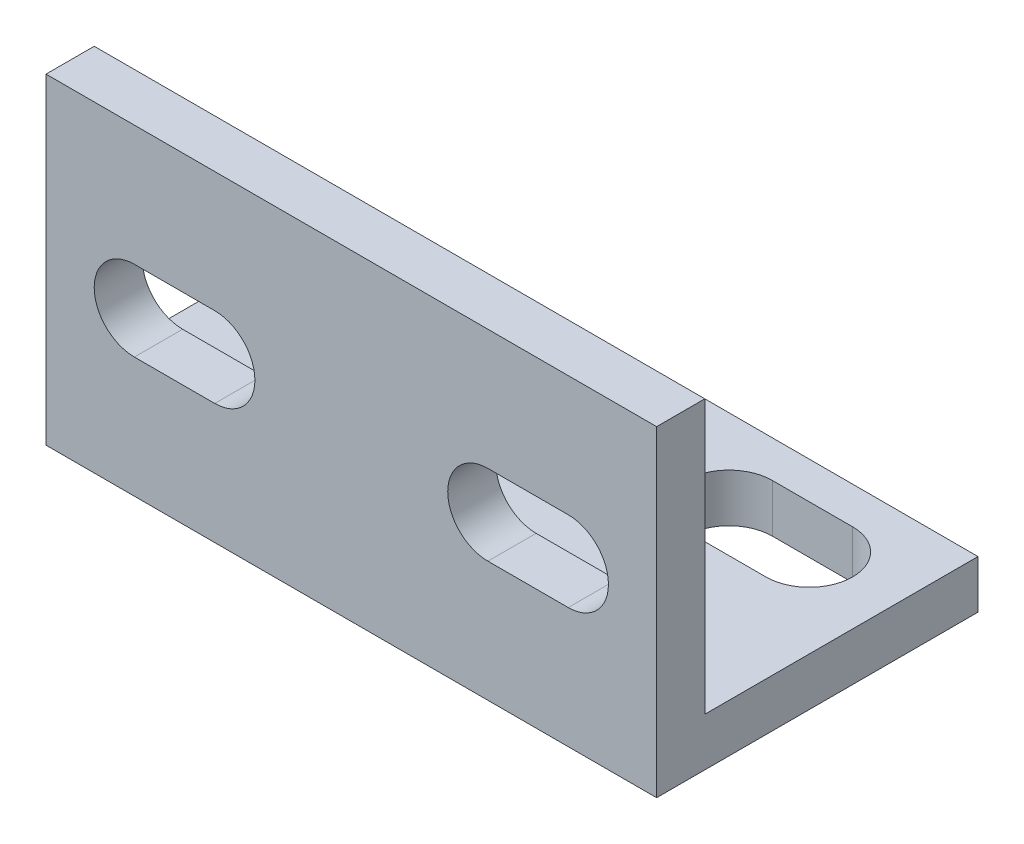
SolidWorks part; units mm, degrees
ref_plane "Front Plane" through (0, 0, 0) normal (0, 0, 1) x (1, 0, 0)
ref_plane "Top Plane" through (0, 0, 0) normal (0, 1, 0) x (1, 0, 0)
ref_plane "Right Plane" through (0, 0, 0) normal (1, 0, 0) x (0, 0, -1)
sketch "Sketch1" plane through (0, 0, 0) normal (1, 0, 0) x (0, 0, -1)
  line L0 (0, 0) -> (-17, 0)
  line L1 (-17, 0) -> (-17, 17)
  line L2 (-17, 17) -> (-20, 17)
  line L3 (-20, 17) -> (-20, -3)
  line L4 (0, 0) -> (0, -3)
  line L5 (0, -3) -> (-20, -3)
  dimension "D1" = 3
  dimension "D2" = 3
  dimension "D3" = 20
  dimension "D4" = 20
extrude "Boss-Extrude1" add sketch "Sketch1" along normal blind 38
sketch "Sketch2" plane through (0, 0, 0) normal (0, 1, 0) x (1, 0, 0)
  line L0 (0, -5) -> (38, -5) construction
  line L1 (0, 0) -> (0, -17) construction
  line L2 (38, 0) -> (38, -17) construction
  line L3 (38, 0) -> (0, 0) construction
  line L4 (5.5, -5) -> (10.5, -5) construction
  line L5 (5.5, -2.3) -> (10.5, -2.3)
  line L6 (5.5, -7.7) -> (10.5, -7.7)
  line L7 (19, 0) -> (19, -17) construction
  line L8 (38, -17) -> (0, -17) construction
  line L9 (32.5, -5) -> (27.5, -5) construction
  line L10 (32.5, -2.3) -> (27.5, -2.3)
  line L11 (32.5, -7.7) -> (27.5, -7.7)
  arc A0 (5.5, -2.3) -> (5.5, -7.7) centre (5.5, -5) ccw
  arc A1 (10.5, -7.7) -> (10.5, -2.3) centre (10.5, -5) ccw
  arc A2 (32.5, -2.3) -> (32.5, -7.7) centre (32.5, -5) cw
  arc A3 (27.5, -7.7) -> (27.5, -2.3) centre (27.5, -5) cw
  point P10 (8, -5)
  point P21 (30, -5)
  dimension "D2" = 2.7
  dimension "D3" = 5
  dimension "D4" = 5.5
  dimension "D1" = 5
extrude "Cut-Extrude1" cut sketch "Sketch2" against normal blind 4
sketch "Sketch3" plane through (0, 0, 17) normal (0, 0, -1) x (-1, 0, 0)
  line L0 (-38, 7) -> (0, 7) construction
  line L4 (-38, 0) -> (-38, 17) construction
  line L5 (0, 0) -> (0, 17) construction
  line L6 (-38, 17) -> (0, 17) construction
  line L7 (-32.5, 7) -> (-27.5, 7) construction
  line L8 (-32.5, 9.5) -> (-27.5, 9.5)
  line L9 (-32.5, 4.5) -> (-27.5, 4.5)
  line L10 (-19, 17) -> (-19, 0) construction
  line L11 (-38, 0) -> (0, 0) construction
  line L12 (-5.5, 7) -> (-10.5, 7) construction
  line L13 (-5.5, 9.5) -> (-10.5, 9.5)
  line L14 (-5.5, 4.5) -> (-10.5, 4.5)
  arc A0 (-32.5, 9.5) -> (-32.5, 4.5) centre (-32.5, 7) ccw
  arc A1 (-27.5, 4.5) -> (-27.5, 9.5) centre (-27.5, 7) ccw
  arc A2 (-5.5, 9.5) -> (-5.5, 4.5) centre (-5.5, 7) cw
  arc A3 (-10.5, 4.5) -> (-10.5, 9.5) centre (-10.5, 7) cw
  point P10 (-30, 7)
  point P21 (-8, 7)
  dimension "D2" = 2.5
  dimension "D4" = 5.5
  dimension "D1" = 10
  dimension "D3" = 5
extrude "Cut-Extrude2" cut sketch "Sketch3" against normal blind 4
